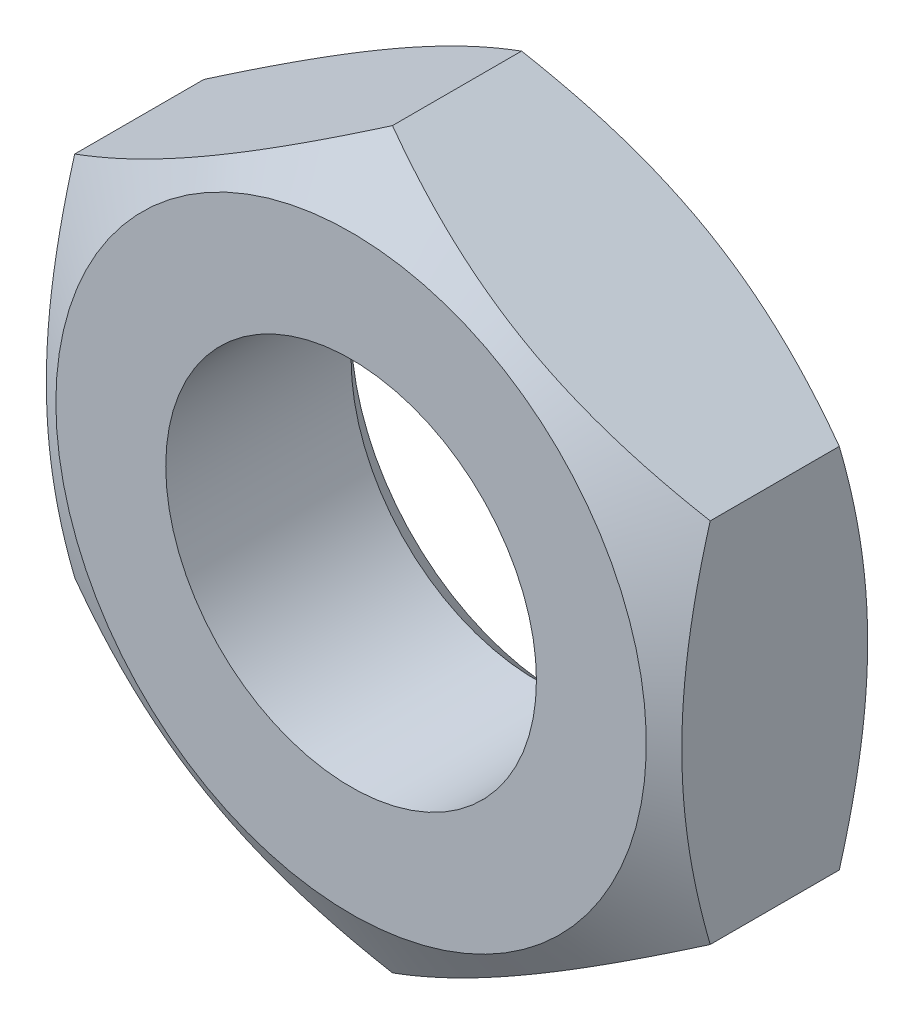
SolidWorks part; units mm, degrees
ref_plane "Спереди" through (0, 0, 0) normal (0, 0, 1) x (1, 0, 0)
ref_plane "Сверху" through (0, 0, 0) normal (0, 1, 0) x (1, 0, 0)
ref_plane "Справа" through (0, 0, 0) normal (1, 0, 0) x (0, 0, -1)
other "Configuration Table"
sketch "Эскиз1" plane through (0, 0, 0) normal (0, 0, 1) x (1, 0, 0)
  line L1 (0, 13.8564) -> (-12, 6.9282)
  line L2 (-12, 6.9282) -> (-12, -6.9282)
  line L3 (-12, -6.9282) -> (0, -13.8564)
  line L4 (0, -13.8564) -> (12, -6.9282)
  line L5 (12, -6.9282) -> (12, 6.9282)
  line L6 (12, 6.9282) -> (0, 13.8564)
  circle A0 centre (0, 0) radius 12 construction
  circle A1 centre (0, 0) radius 7
  dimension "D2" = 14
  dimension "D1" = 24
extrude "Бобышка-Вытянуть1" add sketch "Эскиз1" along normal blind 8
cosmetic thread "Условное изображение резьбы1" parameters "D2"=16
sketch "Эскиз2" plane through (0, 0, 0) normal (1, 0, 0) x (0, 0, -1)
  line L0 (0, 13.8564) -> (-1.5625, 13.8564)
  line L1 (-8, 13.8564) -> (0, 13.8564) construction
  line L2 (-1.5625, 13.8564) -> (0, 11.15)
  line L3 (0, 6.9282) -> (0, 13.8564) construction
  line L4 (0, 11.15) -> (0, 13.8564)
  line L5 (0, 0) -> (-8, 0) construction
  line L6 (0, -6.9282) -> (0, 6.9282) construction
  line L7 (-8, -6.9282) -> (-8, 6.9282) construction
  line L8 (-4, 0) -> (-4, 17.4689) construction
  line L9 (-8, 11.15) -> (-8, 13.8564)
  line L10 (-6.4375, 13.8564) -> (-8, 11.15)
  line L11 (-8, 13.8564) -> (-6.4375, 13.8564)
  dimension "D1" = 30
  dimension "D2" = 22.3
revolve "Вырез-Повернуть1" cut sketch "Эскиз2" angle 360 about L5
chamfer "Фаска1" distance 1 angle 45 1 edges at (7, 0, 0)
